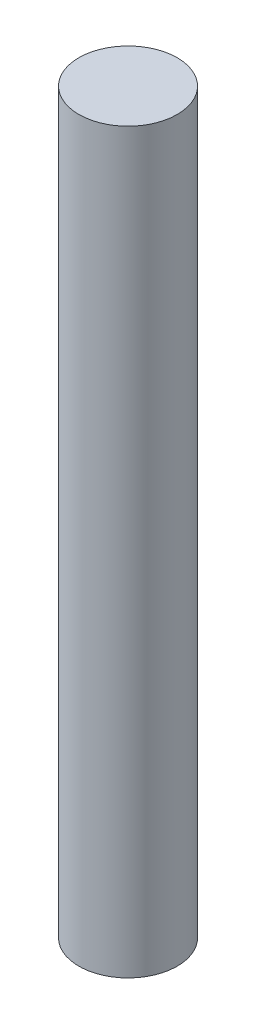
SolidWorks part; units mm, degrees
ref_plane "正面" through (0, 0, 0) normal (0, 0, 1) x (1, 0, 0)
ref_plane "平面" through (0, 0, 0) normal (0, 1, 0) x (1, 0, 0)
ref_plane "右側面" through (0, 0, 0) normal (1, 0, 0) x (0, 0, -1)
sketch "ｽｹｯﾁ1" plane through (0, 0, 0) normal (0, 1, 0) x (1, 0, 0)
  circle A0 centre (0, 0) radius 5
  dimension "D1" = 10
extrude "ﾎﾞｽ - 押し出し1" add sketch "ｽｹｯﾁ1" along normal blind 7
sketch "ｽｹｯﾁ2" plane through (0, 0, 0) normal (0, -1, 0) x (1, 0, 0)
  circle A0 centre (0, 0) radius 5
extrude "ﾎﾞｽ - 押し出し2" add sketch "ｽｹｯﾁ2" along normal blind 68
sketch "ｽｹｯﾁ3" plane through (0, -68, 0) normal (0, -1, 0) x (1, 0, 0)
  circle A0 centre (0, 0) radius 3.5
  dimension "D1" = 7
extrude "ｶｯﾄ - 押し出し1" cut sketch "ｽｹｯﾁ3" against normal blind 20 contours A0
